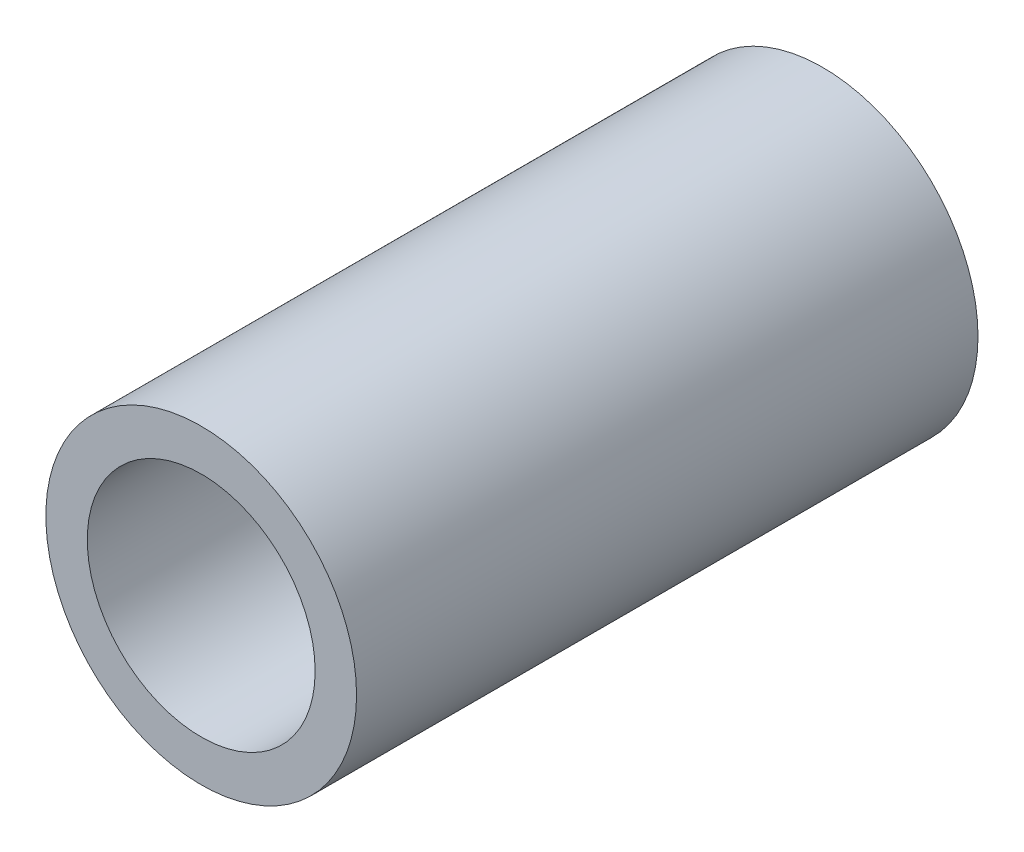
SolidWorks part; units mm, degrees
ref_plane "Front Plane" through (0, 0, 0) normal (0, 0, 1) x (1, 0, 0)
ref_plane "Top Plane" through (0, 0, 0) normal (0, 1, 0) x (1, 0, 0)
ref_plane "Right Plane" through (0, 0, 0) normal (1, 0, 0) x (0, 0, -1)
sketch "Sketch1" plane through (0, 0, 0) normal (0, 0, 1) x (1, 0, 0)
  circle A0 centre (0, 0) radius 30
  dimension "D1" = 60
extrude "Boss-Extrude1" add sketch "Sketch1" along normal blind 120
sketch "Sketch2" plane through (0, 0, 120) normal (0, 0, 1) x (1, 0, 0)
  circle A0 centre (0, 0) radius 22
  circle A1 centre (0, 0) radius 30 construction
  dimension "D1" = 8
extrude "Cut-Extrude1" cut sketch "Sketch2" against normal blind 140
